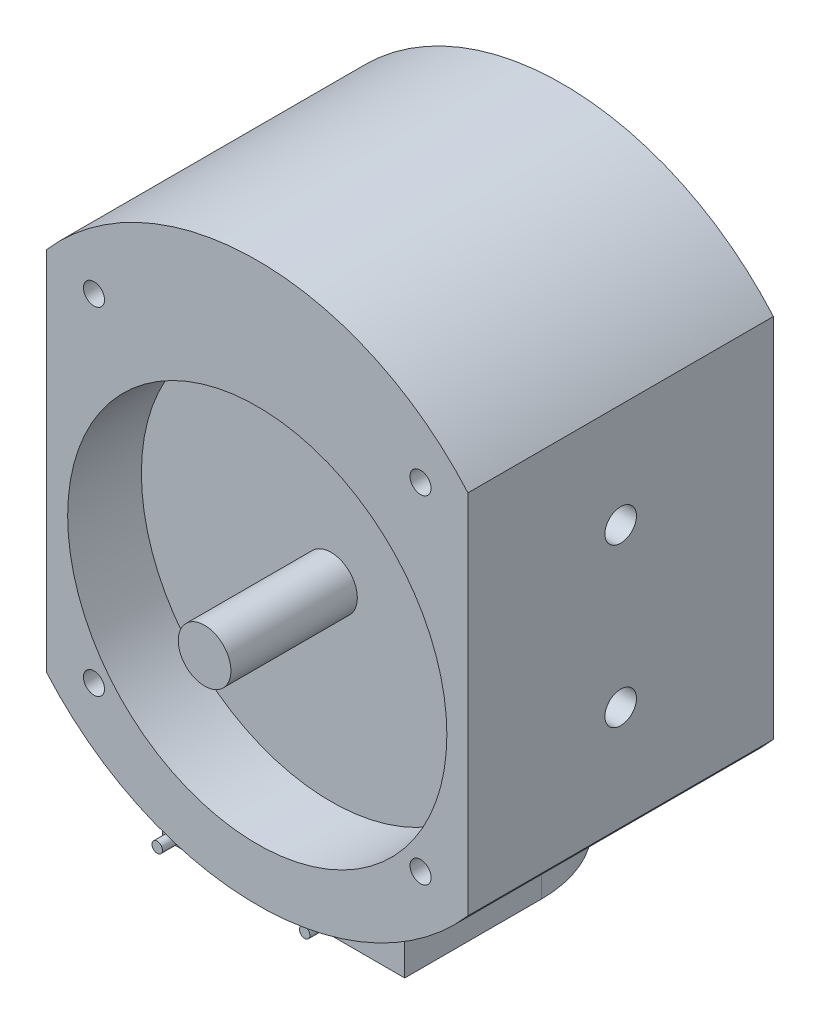
SolidWorks part; units mm, degrees
ref_plane "Front Plane" through (0, 0, 0) normal (0, 0, 1) x (1, 0, 0)
ref_plane "Top Plane" through (0, 0, 0) normal (0, 1, 0) x (1, 0, 0)
ref_plane "Right Plane" through (0, 0, 0) normal (1, 0, 0) x (0, 0, -1)
sketch "Sketch1" plane through (0, 0, 0) normal (0, 0, 1) x (1, 0, 0)
  line L0 (-20, 20.8853) -> (-20, -13.8853)
  line L3 (20, 20.8853) -> (20, -13.8853)
  line L4 (0, 3.5) -> (0, 30) construction
  arc A2 (20, 20.8853) -> (-20, 20.8853) centre (0, 3.5) ccw
  arc A3 (-20, -13.8853) -> (20, -13.8853) centre (0, 3.5) ccw
  dimension "D3" = 3.5
  dimension "D1" = 53
  dimension "D2" = 40
extrude "Boss-Extrude1" add sketch "Sketch1" along normal mid plane 29
ref_plane "Plane2" through (0, -29, 0) normal (0, 1, 0) x (1, 0, 0)
sketch "Sketch3" plane through (0, -29, 0) normal (0, 1, 0) x (1, 0, 0)
  line L0 (-4.5, 14.5) -> (-4.5, -14.5) construction
  line L1 (20, 14.5) -> (-20, 14.5) construction
  line L2 (-20, -14.5) -> (20, -14.5) construction
  line L3 (-11.6589, 14.5) -> (2.6589, 14.5)
  line L8 (7, 5.5) -> (7, -7.5)
  line L9 (7, -7.5) -> (-16, -7.5)
  line L10 (-16, 5.5) -> (-16, -7.5)
  line L12 (-20, -14.5) -> (-20, 14.5) construction
  arc A0 (2.6589, 14.5) -> (7, 5.5) centre (-4.5, 5.5) cw
  arc A1 (-11.6589, 14.5) -> (-16, 5.5) centre (-4.5, 5.5) ccw
  point P15 (-4.5, -7.5)
  dimension "D3" = 11.5
  dimension "D1" = 4
  dimension "D2" = 23
  dimension "D4" = 9
  dimension "D5" = 7
extrude "Boss-Extrude2" add sketch "Sketch3" along normal up to next
sketch "Sketch4" plane through (0, 0, 7.5) normal (0, 0, 1) x (1, 0, 0)
  line L0 (-16, -29) -> (7, -29) construction
  line L1 (7, -22.0588) -> (7, -29) construction
  circle A0 centre (-11.5, -25) radius 0.5
  circle A1 centre (2.5, -25) radius 0.5
  dimension "D1" = 1
  dimension "D2" = 4
  dimension "D3" = 14
  dimension "D4" = 4.5
extrude "Boss-Extrude3" add sketch "Sketch4" along normal blind 5
sketch "Sketch6" plane through (0, 0, 0) normal (0, 0, 1) x (1, 0, 0)
  circle A0 centre (0, 0) radius 2.5
  dimension "D1" = 5
extrude "Boss-Extrude4" add sketch "Sketch6" along normal mid plane 39
sketch "Sketch7" plane through (0, 0, 14.5) normal (0, 0, 1) x (1, 0, 0)
  circle A0 centre (0, 0) radius 18
  circle A1 centre (0, 0) radius 2.5 construction
  circle A2 centre (0, 0) radius 2.5
  dimension "D1" = 36
extrude "Cut-Extrude1" cut sketch "Sketch7" against normal blind 7
sketch "Sketch8" plane through (0, 0, 14.5) normal (0, 0, 1) x (1, 0, 0)
  line L0 (-18.0589, 3.5) -> (0, 3.5) construction
  line L1 (0, 3.5) -> (0, 15.3269) construction
  circle A0 centre (-15.5, 19.5) radius 1
  circle A1 centre (15.5, 19.5) radius 1
  circle A2 centre (15.5, -12.5) radius 1
  circle A3 centre (-15.5, -12.5) radius 1
  arc A4 (20, 20.8853) -> (-20, 20.8853) centre (0, 3.5) ccw construction
  arc A5 (20, 20.8853) -> (-20, 20.8853) centre (0, 3.5) ccw construction
  dimension "D1" = 31
  dimension "D2" = 32
  dimension "D3" = 2
extrude "Cut-Extrude2" cut sketch "Sketch8" against normal through all contours A3 | A0 | A1 | A2
sketch "Sketch9" plane through (20, 0, 0) normal (1, 0, 0) x (0, 0, -1)
  line L0 (-14.5, -13.8853) -> (-14.5, 20.8853) construction
  line L1 (14.5, 30) -> (-14.5, 30) construction
  circle A0 centre (0, 11) radius 1.5
  circle A1 centre (0, -4) radius 1.5
  dimension "D2" = 19
  dimension "D3" = 15
  dimension "D4" = 3
  dimension "D1" = 14.5
extrude "Cut-Extrude3" cut sketch "Sketch9" against normal blind 5
mirror "Mirror1" about plane through (0, 0, 0) normal (1, 0, 0) of "Cut-Extrude3"
